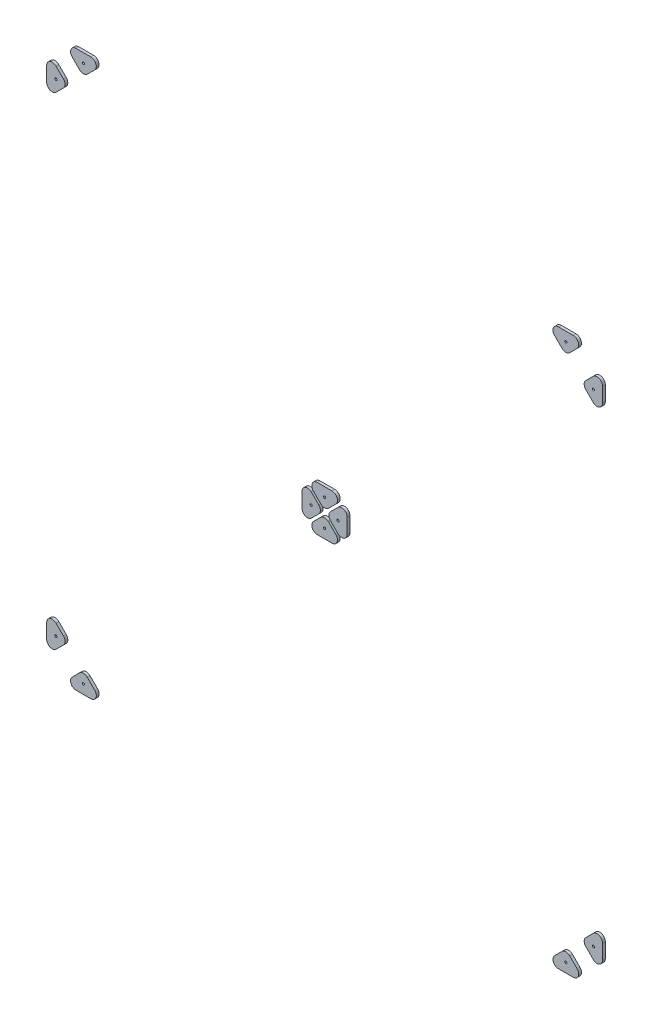
SolidWorks part; units mm, degrees
material "Plain Carbon Steel"
ref_plane "Front Plane" through (0, 0, 0) normal (0, 0, 1) x (1, 0, 0)
ref_plane "Top Plane" through (0, 0, 0) normal (0, 1, 0) x (1, 0, 0)
ref_plane "Right Plane" through (0, 0, 0) normal (1, 0, 0) x (0, 0, -1)
sketch "Sketch1" plane through (0, 0, 0) normal (0, 0, 1) x (1, 0, 0)
  line L0 (549.5147, -584.5147) -> (533.4853, -568.4853)
  line L1 (-600, -605) -> (600, -605) construction
  line L2 (516.5147, -568.4853) -> (500.4853, -584.5147)
  line L3 (508.9706, -605) -> (541.0294, -605)
  line L4 (600.7574, -605) -> (19.0919, -23.3345) construction
  line L5 (449.2426, -605) -> (525, -529.2426) construction
  line L6 (0, 0) -> (0, -680) construction
  line L7 (675, -680) -> (-675, -680) construction
  line L8 (0, 0) -> (602.8787, -602.8787) construction
  line L9 (600.7574, -605) -> (605, -600.7574) construction
  line L10 (605, -508.9706) -> (605, -541.0294)
  line L11 (568.4853, -516.5147) -> (584.5147, -500.4853)
  line L12 (584.5147, -549.5147) -> (568.4853, -533.4853)
  line L13 (-584.5147, -549.5147) -> (-568.4853, -533.4853)
  line L14 (-568.4853, -516.5147) -> (-584.5147, -500.4853)
  line L15 (-605, -508.9706) -> (-605, -541.0294)
  line L16 (-508.9706, -605) -> (-541.0294, -605)
  line L17 (-516.5147, -568.4853) -> (-500.4853, -584.5147)
  line L18 (-549.5147, -584.5147) -> (-533.4853, -568.4853)
  line L19 (0, 0) -> (-724, 0) construction
  line L20 (-724, -424) -> (-724, 424) construction
  line L21 (-549.5147, 584.5147) -> (-533.4853, 568.4853)
  line L22 (-516.5147, 568.4853) -> (-500.4853, 584.5147)
  line L23 (-508.9706, 605) -> (-541.0294, 605)
  line L24 (-605, 508.9706) -> (-605, 541.0294)
  line L25 (-568.4853, 516.5147) -> (-584.5147, 500.4853)
  line L26 (-584.5147, 549.5147) -> (-568.4853, 533.4853)
  line L27 (584.5147, 549.5147) -> (568.4853, 533.4853)
  line L28 (568.4853, 516.5147) -> (584.5147, 500.4853)
  line L29 (605, 508.9706) -> (605, 541.0294)
  line L30 (508.9706, 605) -> (541.0294, 605)
  line L31 (516.5147, 568.4853) -> (500.4853, 584.5147)
  line L32 (549.5147, 584.5147) -> (533.4853, 568.4853)
  line L33 (525, -605) -> (525, -564.9706) construction
  line L34 (0, -49.2426) -> (0, -4.2426) construction
  line L35 (16.0294, -49.2426) -> (-16.0294, -49.2426)
  line L36 (600.7574, -605) -> (19.0919, -23.3345) construction
  line L37 (-19.0919, -23.3345) -> (-600.7574, -605) construction
  line L38 (-24.5147, -28.7574) -> (-8.4853, -12.7279)
  line L39 (8.4853, -12.7279) -> (24.5147, -28.7574)
  line L40 (49.2426, 0) -> (4.2426, 0) construction
  line L41 (12.7279, -8.4853) -> (28.7574, -24.5147)
  line L42 (28.7574, 24.5147) -> (12.7279, 8.4853)
  line L43 (49.2426, -16.0294) -> (49.2426, 16.0294)
  line L44 (0, 0) -> (678.5355, 678.5355) construction
  line L45 (0, 49.2426) -> (0, 4.2426) construction
  line L46 (-49.2426, 0) -> (-4.2426, 0) construction
  line L47 (-16.0294, 49.2426) -> (16.0294, 49.2426)
  line L48 (24.5147, 28.7574) -> (8.4853, 12.7279)
  line L49 (-8.4853, 12.7279) -> (-24.5147, 28.7574)
  line L50 (-12.7279, 8.4853) -> (-28.7574, 24.5147)
  line L51 (-28.7574, -24.5147) -> (-12.7279, -8.4853)
  line L52 (-49.2426, 16.0294) -> (-49.2426, -16.0294)
  line L53 (541.5, -576.5) -> (556.8787, -561.1213) construction
  line L54 (508.5, -576.5) -> (493.1213, -561.1213) construction
  line L55 (525, -564.9706) -> (525, -560) construction
  line L56 (525, -560) -> (516.5147, -568.4853) construction
  line L57 (525, -560) -> (525, -605) construction
  circle A0 centre (525, -585) radius 2.4
  arc A1 (500.4853, -584.5147) -> (508.9706, -605) centre (508.9706, -593) ccw
  arc A2 (533.4853, -568.4853) -> (516.5147, -568.4853) centre (525, -576.9706) ccw
  arc A3 (549.5147, -584.5147) -> (541.0294, -605) centre (541.0294, -593) cw
  arc A4 (584.5147, -549.5147) -> (605, -541.0294) centre (593, -541.0294) ccw
  arc A5 (568.4853, -533.4853) -> (568.4853, -516.5147) centre (576.9706, -525) cw
  arc A6 (584.5147, -500.4853) -> (605, -508.9706) centre (593, -508.9706) cw
  circle A7 centre (585, -525) radius 2.4
  circle A8 centre (-585, -525) radius 2.4
  arc A9 (-584.5147, -500.4853) -> (-605, -508.9706) centre (-593, -508.9706) ccw
  arc A10 (-568.4853, -533.4853) -> (-568.4853, -516.5147) centre (-576.9706, -525) ccw
  arc A11 (-584.5147, -549.5147) -> (-605, -541.0294) centre (-593, -541.0294) cw
  arc A12 (-549.5147, -584.5147) -> (-541.0294, -605) centre (-541.0294, -593) ccw
  arc A13 (-533.4853, -568.4853) -> (-516.5147, -568.4853) centre (-525, -576.9706) cw
  arc A14 (-500.4853, -584.5147) -> (-508.9706, -605) centre (-508.9706, -593) cw
  circle A15 centre (-525, -585) radius 2.4
  circle A16 centre (-525, 585) radius 2.4
  arc A17 (-500.4853, 584.5147) -> (-508.9706, 605) centre (-508.9706, 593) ccw
  arc A18 (-533.4853, 568.4853) -> (-516.5147, 568.4853) centre (-525, 576.9706) ccw
  arc A19 (-549.5147, 584.5147) -> (-541.0294, 605) centre (-541.0294, 593) cw
  arc A20 (-584.5147, 549.5147) -> (-605, 541.0294) centre (-593, 541.0294) ccw
  arc A21 (-568.4853, 533.4853) -> (-568.4853, 516.5147) centre (-576.9706, 525) cw
  arc A22 (-584.5147, 500.4853) -> (-605, 508.9706) centre (-593, 508.9706) cw
  circle A23 centre (-585, 525) radius 2.4
  circle A24 centre (585, 525) radius 2.4
  arc A25 (584.5147, 500.4853) -> (605, 508.9706) centre (593, 508.9706) ccw
  arc A26 (568.4853, 533.4853) -> (568.4853, 516.5147) centre (576.9706, 525) ccw
  arc A27 (584.5147, 549.5147) -> (605, 541.0294) centre (593, 541.0294) cw
  arc A28 (549.5147, 584.5147) -> (541.0294, 605) centre (541.0294, 593) ccw
  arc A29 (533.4853, 568.4853) -> (516.5147, 568.4853) centre (525, 576.9706) cw
  arc A30 (500.4853, 584.5147) -> (508.9706, 605) centre (508.9706, 593) cw
  circle A31 centre (525, 585) radius 2.4
  arc A32 (8.4853, -12.7279) -> (-8.4853, -12.7279) centre (0, -21.2132) ccw
  arc A33 (-16.0294, -49.2426) -> (-24.5147, -28.7574) centre (-16.0294, -37.2426) cw
  arc A34 (16.0294, -49.2426) -> (24.5147, -28.7574) centre (16.0294, -37.2426) ccw
  circle A35 centre (0, -29.2426) radius 2.4
  circle A36 centre (29.2426, 0) radius 2.4
  arc A37 (49.2426, -16.0294) -> (28.7574, -24.5147) centre (37.2426, -16.0294) cw
  arc A38 (49.2426, 16.0294) -> (28.7574, 24.5147) centre (37.2426, 16.0294) ccw
  arc A39 (12.7279, -8.4853) -> (12.7279, 8.4853) centre (21.2132, 0) cw
  arc A40 (680, 675) -> (675, 680) centre (675, 675) ccw construction
  arc A41 (-8.4853, 12.7279) -> (8.4853, 12.7279) centre (0, 21.2132) ccw
  arc A42 (16.0294, 49.2426) -> (24.5147, 28.7574) centre (16.0294, 37.2426) cw
  arc A43 (-16.0294, 49.2426) -> (-24.5147, 28.7574) centre (-16.0294, 37.2426) ccw
  circle A44 centre (0, 29.2426) radius 2.4
  circle A45 centre (-29.2426, 0) radius 2.4
  arc A46 (-49.2426, 16.0294) -> (-28.7574, 24.5147) centre (-37.2426, 16.0294) cw
  arc A47 (-49.2426, -16.0294) -> (-28.7574, -24.5147) centre (-37.2426, -16.0294) ccw
  arc A48 (-12.7279, 8.4853) -> (-12.7279, -8.4853) centre (-21.2132, 0) cw
  point P13 (480, -605)
  point P18 (570, -605)
  point P38 (605, -570)
  point P39 (605, -480)
  point P62 (-605, -480)
  point P63 (-605, -570)
  point P64 (-570, -605)
  point P65 (-480, -605)
  point P113 (-480, 605)
  point P114 (-570, 605)
  point P115 (-605, 570)
  point P116 (-605, 480)
  point P117 (605, 480)
  point P118 (605, 570)
  point P119 (570, 605)
  point P120 (480, 605)
  point P137 (-45, -49.2426)
  point P140 (45, -49.2426)
  point P156 (49.2426, -45)
  point P157 (49.2426, 45)
  point P188 (45, 49.2426)
  point P189 (-45, 49.2426)
  point P190 (-49.2426, 45)
  point P191 (-49.2426, -45)
  dimension "D4" = 4.8
  dimension "D5" = 12
  dimension "D6" = 12
  dimension "D7" = 4.8
  dimension "D1" = 45
  dimension "D2" = 45
  dimension "D3" = 20
  dimension "D8" = 20
extrude "Boss-Extrude1" add sketch "Sketch1" against normal blind 6
